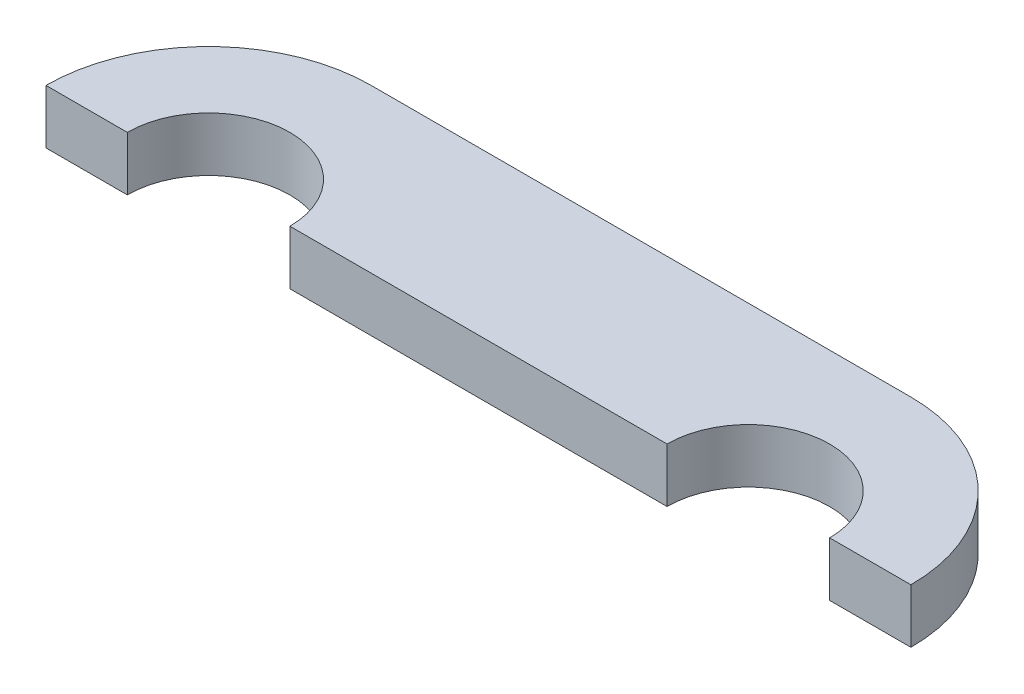
SolidWorks part; units mm, degrees
ref_plane "Front Plane" through (0, 0, 0) normal (0, 0, 1) x (1, 0, 0)
ref_plane "Top Plane" through (0, 0, 0) normal (0, 1, 0) x (1, 0, 0)
ref_plane "Right Plane" through (0, 0, 0) normal (1, 0, 0) x (0, 0, -1)
sketch "Sketch1" plane through (0, 0, 0) normal (0, 1, 0) x (1, 0, 0)
  line L0 (-6.35, 4.7625) -> (9.398, 4.7621)
  circle A0 centre (-6.35, 0) radius 2.3813
  circle A1 centre (9.4615, 0) radius 2.3813
  circle A2 centre (-6.35, 0) radius 4.7625
  circle A3 centre (9.4615, 0) radius 4.7625
  circle A4 centre (1.524, -6.35) radius 2.3812
  circle A5 centre (1.524, -6.35) radius 5.353
  arc A6 (-8.1764, -4.3984) -> (-3.1815, -8.9019) centre (-12.0416, -13.707) cw
  arc A7 (6.5046, -8.3115) -> (10.6745, -4.6054) centre (12.2461, -10.5726) cw
  dimension "D1" = 4.7625
  dimension "D2" = 6.35
  dimension "D3" = 0
  dimension "D5" = 4.7625
  dimension "D6" = 9.525
  dimension "D7" = 9.525
  dimension "D8" = 4.7625
  dimension "D9" = 7.874
  dimension "D10" = 6.35
  dimension "D4" = 15.8115
extrude "Boss-Extrude1" add sketch "Sketch1" along normal blind 1.5875 contours A2 A0 | A2 A6 A5 | A5 A3 L0 A2 | A3 A1 | A5 A7 A3 | A5 A4
sketch "Sketch2" plane through (0, 0, 0) normal (0, -1, 0) x (1, 0, 0)
  circle A0 centre (1.524, 6.35) radius 3.175
  dimension "D1" = 6.35
extrude "Boss-Extrude2" add sketch "Sketch2" along normal blind 1.5875
sketch "Sketch3" plane through (0, 0, 0) normal (0, 1, 0) x (1, 0, 0)
  circle A0 centre (1.524, -6.35) radius 2.3812
extrude "Boss-Extrude3" add sketch "Sketch3" along normal blind 19.05
sketch "Sketch4" plane through (0, 19.05, 0) normal (0, 1, 0) x (1, 0, 0)
  circle A0 centre (1.524, -6.35) radius 3.175
  dimension "D1" = 6.35
extrude "Boss-Extrude4" add sketch "Sketch4" against normal blind 1.5875
sketch "Sketch5" plane through (0, 17.4625, 0) normal (0, -1, 0) x (1, 0, 0)
  line L0 (-6.35, -4.7625) -> (9.4615, -4.7625)
  circle A0 centre (-6.35, 0) radius 2.3813
  circle A1 centre (9.4615, 0) radius 2.3813
  circle A2 centre (1.524, 6.35) radius 5.353
  circle A3 centre (-6.35, 0) radius 4.7625
  circle A4 centre (9.4615, 0) radius 4.7625
  arc A5 (-8.1764, 4.3984) -> (-3.1815, 8.9019) centre (-12.0416, 13.707) ccw
  arc A6 (6.5046, 8.3115) -> (10.6745, 4.6054) centre (12.2461, 10.5726) ccw
  circle M1 centre (1.524, 6.35) radius 2.3812
  circle M2 centre (1.524, 6.35) radius 3.175
extrude "Boss-Extrude5" add sketch "Sketch5" along normal blind 1.5875 separate body contours A2 M2 | A6 A2 A4 | A4 A1 | A5 A3 A2 | A4 A2 A3 L0 | A3 A0 | M2 M1
sketch "Sketch6" plane through (0, 19.05, 0) normal (0, 1, 0) x (1, 0, 0)
  circle A0 centre (1.524, -6.35) radius 2.3813
  dimension "D1" = 4.7625
extrude "Cut-Extrude1" cut sketch "Sketch6" against normal through all
sketch "Sketch7" plane through (0, 1.5875, 0) normal (0, 1, 0) x (1, 0, 0)
  line L1 (20.3943, 5.8739) -> (-20.2966, 5.8739)
  line L2 (20.3943, 5.8739) -> (20.3943, -14.1314)
  line L3 (20.3943, -14.1314) -> (-20.2966, -14.1314)
  line L4 (-20.2966, 5.8739) -> (-20.2966, -14.1314)
extrude "Cut-Extrude2" cut sketch "Sketch7" against normal through all
sketch "Sketch8" plane through (0, 17.4625, 0) normal (0, 1, 0) x (1, 0, 0)
  line L0 (-11.1125, 0) -> (14.224, 0)
  line L1 (14.224, 0) -> (14.224, 6.4373)
  line L2 (14.224, 6.4373) -> (-11.1125, 6.4373)
  line L3 (-11.1125, 6.4373) -> (-11.1125, 0)
  line L4 (-11.1125, 0) -> (-11.118, -0.0459)
  line L5 (-11.118, -0.0459) -> (-11.118, -13.7921)
  line L6 (-11.118, -13.7921) -> (14.224, -13.7921)
  line L7 (14.224, -13.7921) -> (14.224, 0)
  line L8 (14.224, 0) -> (14.2295, -0.0215)
  arc A0 (-6.35, 4.7625) -> (-8.1764, -4.3984) centre (-6.35, 0) ccw construction
  arc A1 (10.6745, -4.6054) -> (9.4615, 4.7625) centre (9.4615, 0) ccw construction
  arc M1 (-8.1764, -4.3984) -> (-3.1815, -8.9019) centre (-12.0416, -13.707) cw
  arc M2 (-3.1815, -8.9019) -> (6.5046, -8.3115) centre (1.524, -6.35) ccw
  arc M3 (6.5046, -8.3115) -> (10.6745, -4.6054) centre (12.2461, -10.5726) cw
  arc M4 (10.6745, -4.6054) -> (9.4615, 4.7625) centre (9.4615, 0) ccw
  arc M6 (-6.35, 4.7625) -> (-8.1764, -4.3984) centre (-6.35, 0) ccw
  circle M7 centre (1.524, -6.35) radius 2.3812
  circle M8 centre (9.4615, 0) radius 2.3813
  circle M9 centre (-6.35, 0) radius 2.3813
extrude "Cut-Extrude3" cut sketch "Sketch8" against normal through all both and the other way through all contours M7 | L0 M6 M1 M2 M3 M4 M8 M9 M7
